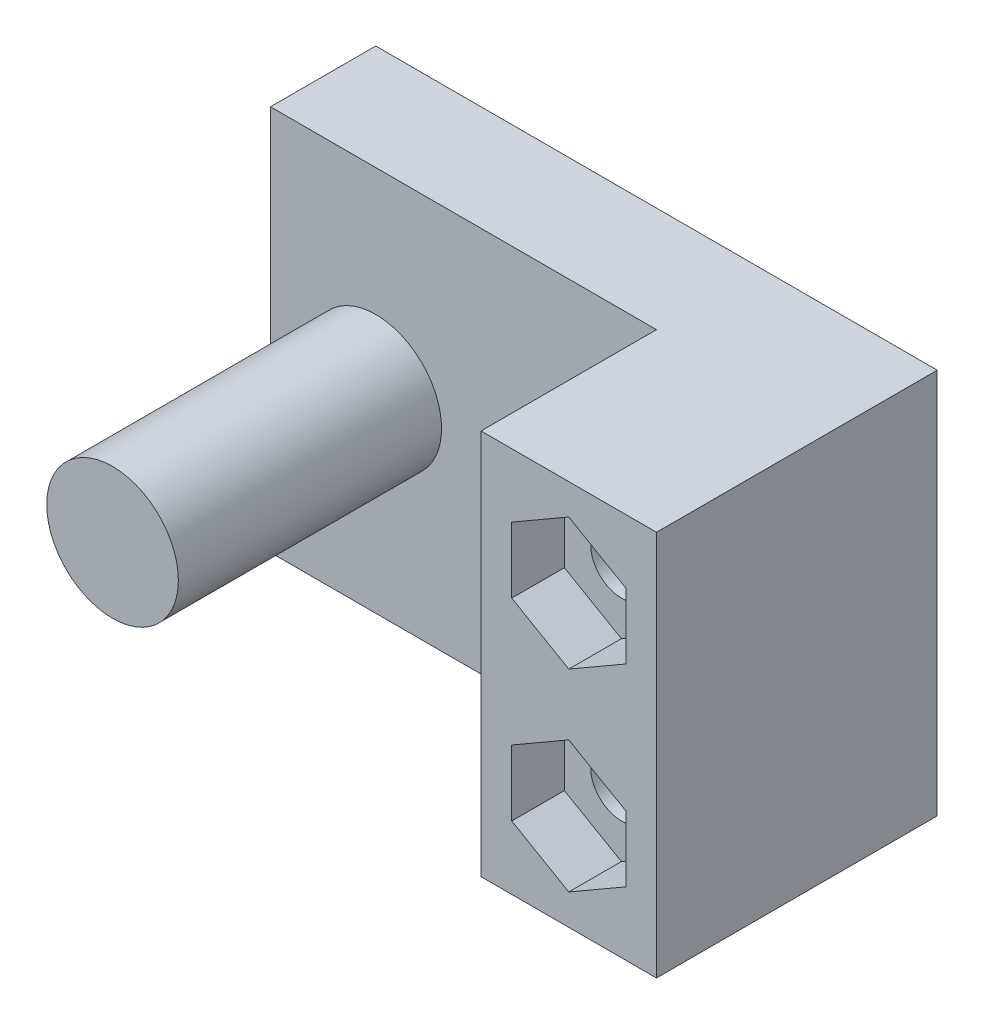
SolidWorks part; units mm, degrees
ref_plane "Front Plane" through (0, 0, 0) normal (0, 0, 1) x (1, 0, 0)
ref_plane "Top Plane" through (0, 0, 0) normal (0, 1, 0) x (1, 0, 0)
ref_plane "Right Plane" through (0, 0, 0) normal (1, 0, 0) x (0, 0, -1)
sketch "Sketch2" plane through (0, 0, 0) normal (0, 1, 0) x (1, 0, 0)
  line L0 (23, 0) -> (-9, 0)
  line L1 (23, 0) -> (23, -16)
  line L2 (23, -16) -> (13, -16)
  line L3 (13, -16) -> (13, -6)
  line L4 (13, -6) -> (-9, -6)
  line L5 (-9, 0) -> (-9, -6)
  dimension "D1" = 10
  dimension "D2" = 13
  dimension "D3" = 22
  dimension "D4" = 16
  dimension "D5" = 6
extrude "Boss-Extrude1" add sketch "Sketch2" along normal blind 22
sketch "Sketch3" plane through (0, 0, 6) normal (0, 0, 1) x (1, 0, 0)
  line L0 (-9, 11) -> (13, 11) construction
  line L2 (13, 22) -> (13, 0) construction
  line L3 (-3, 15) -> (-3, 0) construction
  line L5 (-9, 22) -> (-9, 0) construction
  circle A0 centre (-3, 11) radius 3.75
  dimension "D1" = 7.5
  dimension "D2" = 6
extrude "Boss-Extrude2" add sketch "Sketch3" along normal blind 15
sketch "Sketch7" plane through (0, 0, 16) normal (0, 0, 1) x (1, 0, 0)
  line L0 (18, 22) -> (18, 0) construction
  line L1 (13, 22) -> (23, 22) construction
  line L2 (13, 0) -> (23, 0) construction
  circle A0 centre (18, 16.5) radius 1.75
  circle A1 centre (18, 5.5) radius 1.75
  dimension "D1" = 3.5
  dimension "D2" = 5.5
  dimension "D3" = 5.5
extrude "Cut-Extrude3" cut sketch "Sketch7" against normal blind 6
sketch "Sketch8" plane through (0, 0, 16) normal (0, 0, 1) x (1, 0, 0)
  line L0 (23, 22) -> (23, 0) construction
  line L1 (21.25, 14.6236) -> (21.25, 18.3764)
  line L2 (21.25, 18.3764) -> (18, 20.2528)
  line L3 (18, 20.2528) -> (14.75, 18.3764)
  line L4 (14.75, 18.3764) -> (14.75, 14.6236)
  line L5 (14.75, 14.6236) -> (18, 12.7472)
  line L6 (18, 12.7472) -> (21.25, 14.6236)
  line L7 (21.25, 3.6236) -> (21.25, 7.3764)
  line L8 (21.25, 7.3764) -> (18, 9.2528)
  line L9 (18, 9.2528) -> (14.75, 7.3764)
  line L10 (14.75, 7.3764) -> (14.75, 3.6236)
  line L11 (14.75, 3.6236) -> (18, 1.7472)
  line L12 (18, 1.7472) -> (21.25, 3.6236)
  circle A0 centre (18, 16.5) radius 3.25 construction
  circle A1 centre (18, 5.5) radius 3.25 construction
  dimension "D1" = 6.5
extrude "Cut-Extrude4" cut sketch "Sketch8" against normal blind 3
